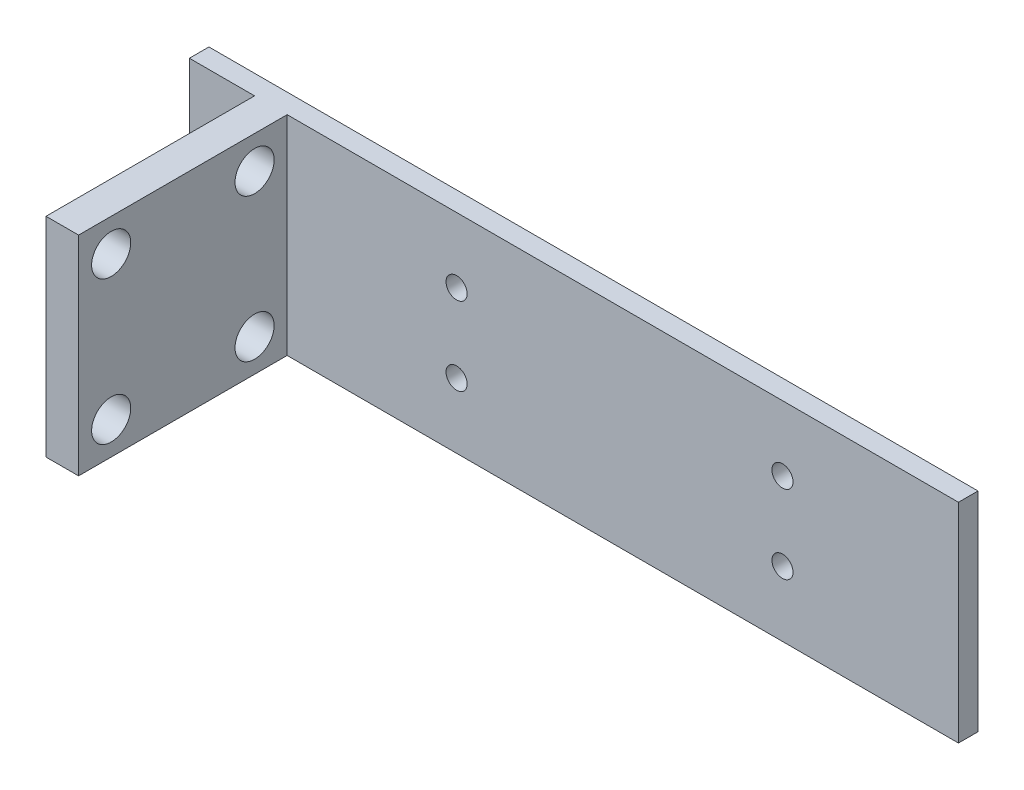
SolidWorks part; units mm, degrees
ref_plane "前视基准面" through (0, 0, 0) normal (0, 0, 1) x (1, 0, 0)
ref_plane "上视基准面" through (0, 0, 0) normal (0, 1, 0) x (1, 0, 0)
ref_plane "右视基准面" through (0, 0, 0) normal (1, 0, 0) x (0, 0, -1)
sketch "草图1" plane through (0, 0, 0) normal (0, 0, 1) x (1, 0, 0)
  line L1 (-71.2816, 22.717) -> (46.7184, 22.717)
  line L2 (-71.2816, 22.717) -> (-71.2816, -9.283)
  line L3 (-71.2816, -9.283) -> (46.7184, -9.283)
  line L4 (46.7184, 22.717) -> (46.7184, -9.283)
  dimension "D1" = 118
  dimension "D2" = 32
extrude "凸台-拉伸1" add sketch "草图1" along normal blind 3
sketch "草图2" plane through (0, 0, 3) normal (0, 0, 1) x (1, 0, 0)
  line L0 (-71.2816, 22.717) -> (-71.2816, -9.283) construction
  line L1 (46.7184, 22.717) -> (-71.2816, 22.717) construction
  line L2 (-71.2816, -9.283) -> (46.7184, -9.283) construction
  circle A0 centre (-30.2816, 12.717) radius 1.62
  circle A1 centre (-30.2816, 0.717) radius 1.62
  circle A2 centre (19.7184, 12.717) radius 1.62
  circle A3 centre (19.7184, 0.717) radius 1.62
  dimension "D1" = 3.24
  dimension "D2" = 41
  dimension "D3" = 10
  dimension "D4" = 3.24
  dimension "D5" = 10
  dimension "D6" = 41
  dimension "D7" = 3.24
  dimension "D8" = 50
  dimension "D9" = 3.24
extrude "切除-拉伸1" cut sketch "草图2" against normal blind 3
sketch "草图3" plane through (0, 0, 3) normal (0, 0, 1) x (1, 0, 0)
  line L0 (-71.2816, -9.283) -> (46.7184, -9.283) construction
  line L1 (-61.2816, 22.717) -> (-56.2816, 22.717)
  line L2 (-61.2816, 22.717) -> (-61.2816, -9.283)
  line L3 (-61.2816, -9.283) -> (-56.2816, -9.283)
  line L4 (-56.2816, 22.717) -> (-56.2816, -9.283)
  line L5 (-71.2816, 22.717) -> (-71.2816, -9.283) construction
  dimension "D1" = 5
  dimension "D2" = 10
extrude "凸台-拉伸2" add sketch "草图3" along normal blind 32
sketch "草图4" plane through (-71.2816, 0, 0) normal (-1, 0, 0) x (0, 0, 1)
  line L0 (35, 22.717) -> (35, -9.283) construction
  line L1 (3, 22.717) -> (0, 22.717) construction
  line L2 (3, -9.283) -> (0, -9.283) construction
  line L3 (0, 22.717) -> (0, -9.283) construction
  circle A0 centre (30, 17.717) radius 3
  circle A1 centre (30, -4.283) radius 3
  circle A2 centre (8, 17.717) radius 3
  circle A3 centre (8, -4.283) radius 3
  dimension "D1" = 5
  dimension "D3" = 5
  dimension "D4" = 5
  dimension "D5" = 8
  dimension "D2" = 5
extrude "切除-拉伸2" cut sketch "草图4" against normal blind 32
